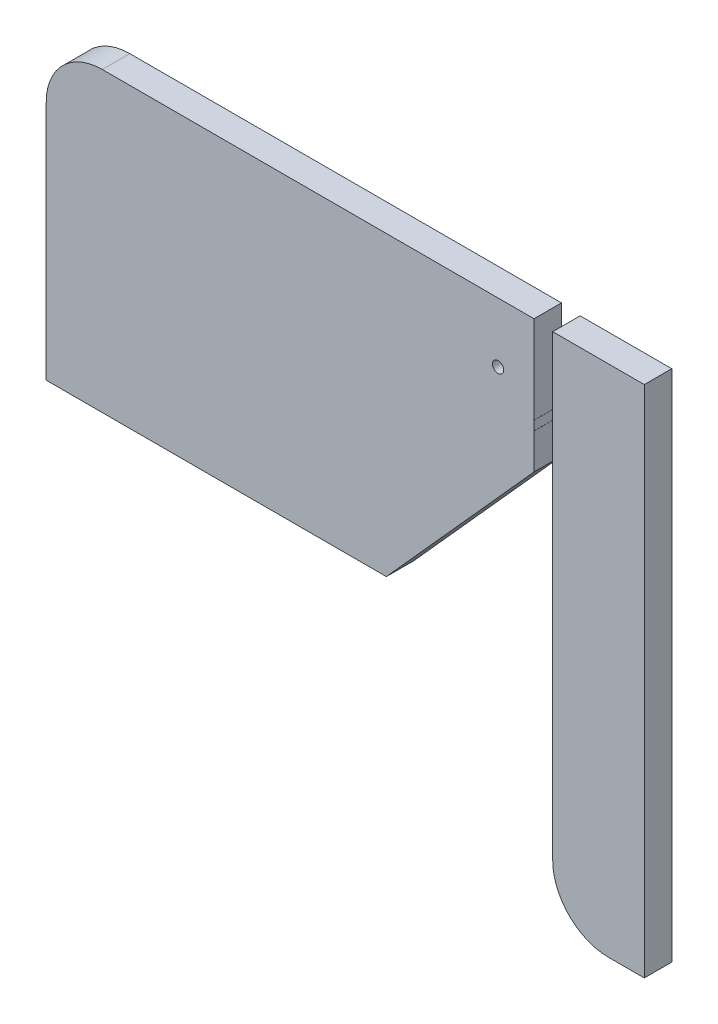
SolidWorks part; units mm, degrees
ref_plane "Front Plane" through (0, 0, 0) normal (0, 0, 1) x (1, 0, 0)
ref_plane "Top Plane" through (0, 0, 0) normal (0, 1, 0) x (1, 0, 0)
ref_plane "Right Plane" through (0, 0, 0) normal (1, 0, 0) x (0, 0, -1)
sketch "Model" plane through (0, 0, 0) normal (0, 0, 1) x (1, 0, 0)
  line L0 (0.3, 13.4) -> (0.3, 26.3)
  line L1 (3.3, 29.3) -> (26.4, 29.3)
  line L2 (18.5, 13.4) -> (18.1997, 13.4)
  line L3 (18.1997, 13.4) -> (16.4, 13.4)
  line L4 (15.7, 13.4) -> (11.4, 13.4)
  line L5 (11.4, 13.4) -> (2.2, 13.4)
  line L6 (2.2, 13.4) -> (0.3, 13.4)
  line L7 (18.5, 13.4) -> (26.4, 22.2)
  line L8 (26.4, 22.2) -> (26.4, 24.1)
  line L9 (26.4, 24.1025) -> (26.4, 29.3)
  line L18 (27.4, 29.2) -> (27.4, 24.1025)
  line L19 (27.4, 24.1025) -> (27.4, 6.2)
  line L20 (27.4, 6.2) -> (27.4, 4.7)
  line L21 (30.4, 1.7) -> (32.3, 1.7)
  line L22 (32.3, 29.2) -> (32.3, 1.7)
  line L23 (32.3, 29.2) -> (27.4, 29.2)
  line L29 (16.4, 13.4) -> (15.7, 13.4)
  arc A0 (3.3, 29.3) -> (0.3, 26.3) centre (3.3, 26.3) ccw
  arc A1 (27.4, 4.7) -> (30.4, 1.7) centre (30.4, 4.7) ccw
  circle A2 centre (24.475, 26.1) radius 0.3
  arc A3 (27.4, 24.5975) -> (27.4, 24.6025) centre (27.4, 24.6) ccw
  arc A4 (26.4, 24.6025) -> (26.4, 24.5975) centre (26.4, 24.6) ccw
  arc A5 (26.4, 24.1025) -> (26.4, 24.0975) centre (26.4, 24.1) ccw
  arc A6 (27.4, 24.0975) -> (27.4, 24.1025) centre (27.4, 24.1) ccw
  arc A10 (18.2, 13.4) -> (18.1997, 13.4) centre (18.1999, 13.4) ccw
  arc A11 (17.7, 13.4) -> (17.6997, 13.4) centre (17.6998, 13.4) ccw
  arc A13 (15.7, 13.4) -> (15.7, 13.3998) centre (15.7, 13.3999) ccw
  arc A14 (16.4, 13.4) -> (16.4, 13.4002) centre (16.4, 13.4001) ccw
extrude "Boss-Extrude1" add sketch "Model" along normal blind 1.47
